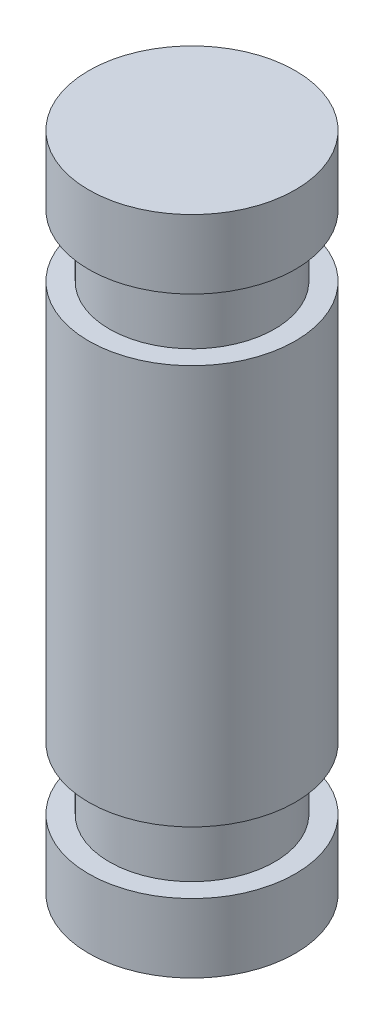
SolidWorks part; units mm, degrees
material "Plain Carbon Steel"
ref_plane "XY" through (0, 0, 0) normal (1, 0, 0) x (0, 1, 0)
ref_plane "XZ" through (0, 0, 0) normal (0, 0, 1) x (0, 1, 0)
ref_plane "YZ" through (0, 0, 0) normal (0, 1, 0) x (-1, 0, 0)
sketch "Sketch1" plane through (0, 0, 0) normal (1, 0, 0) x (0, 1, 0)
  line L0 (0, 0) -> (4.8, 0)
  line L1 (55, 0) -> (-55, 0) construction
  line L2 (4.8, 0) -> (4.8, 1.5)
  line L3 (4.8, 1.5) -> (3.8, 1.5)
  line L4 (-2.9, 1.5) -> (-2.9, 1.2)
  line L5 (-2.9, 1.2) -> (-3.8, 1.2)
  line L7 (-3.8, 1.2) -> (-3.8, 1.5)
  line L8 (-3.8, 1.5) -> (-4.8, 1.5)
  line L9 (-4.8, 1.5) -> (-4.8, 0)
  line L10 (-4.8, 0) -> (0, 0)
  line L11 (4.8, 0) -> (51.7835, 0) construction
  line L12 (2.9, 1.5) -> (2.9, 1.2)
  line L13 (2.9, 1.2) -> (3.8, 1.2)
  line L14 (3.8, 1.2) -> (3.8, 1.5)
  line L15 (2.9, 1.5) -> (-2.9, 1.5)
  point P10 (3.4159, 0)
  point P11 (0, 0)
  point P19 (0, 0)
  point P20 (0, 0)
  point P21 (7.6, 1.2)
  point P23 (0, 1.5)
  dimension "D1" = 1
  dimension "D2" = 3
  dimension "D3" = 0.9
  dimension "D6" = 0.9
  dimension "D7" = 5.8
  dimension "D8" = 2.4
revolve "Revolve1" add sketch "Sketch1" angle 360 about L11
